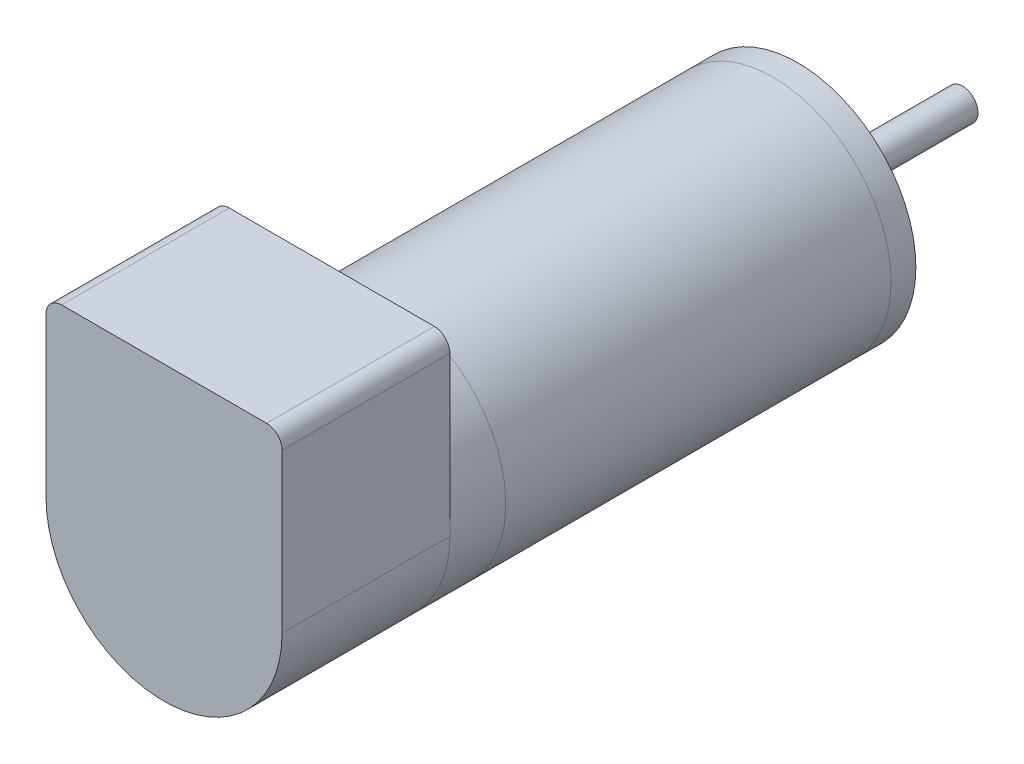
SolidWorks part; units mm, degrees
ref_plane "Front Plane" through (0, 0, 0) normal (0, 0, 1) x (1, 0, 0)
ref_plane "Top Plane" through (0, 0, 0) normal (0, 1, 0) x (1, 0, 0)
ref_plane "Right Plane" through (0, 0, 0) normal (1, 0, 0) x (0, 0, -1)
sketch "Sketch1" plane through (0, 0, 0) normal (1, 0, 0) x (0, 0, -1)
  line L0 (0, 0) -> (101.5, 0) construction
  line L1 (0, 0) -> (0, 19)
  line L2 (0, 19) -> (75, 19)
  line L3 (75, 19) -> (75, 6.25)
  line L4 (75, 6.25) -> (76.5, 6.25)
  line L5 (76.5, 6.25) -> (76.5, 2.5)
  line L6 (76.5, 2.5) -> (101.5, 2.5)
  line L7 (101.5, 2.5) -> (101.5, 0)
  line L8 (0, 0) -> (101.5, 0)
  dimension "D1" = 19
  dimension "D2" = 75
  dimension "D3" = 6.25
  dimension "D4" = 1.5
  dimension "D5" = 25
  dimension "D6" = 2.5
revolve "Revolve1" add sketch "Sketch1" angle 360 about L0
sketch "Sketch2" plane through (0, 0, 0) normal (0, 0, 1) x (1, 0, 0)
  line L0 (-19, 0) -> (-19, 25.5)
  line L1 (-16.5, 28) -> (16.5, 28)
  line L2 (19, 25.5) -> (19, 0)
  circle A0 centre (0, 0) radius 19 construction
  arc A1 (-19, 0) -> (19, 0) centre (0, 0) ccw
  arc A2 (19, 25.5) -> (16.5, 28) centre (16.5, 25.5) ccw
  arc A3 (-19, 25.5) -> (-16.5, 28) centre (-16.5, 25.5) cw
  point P5 (0, -19)
  dimension "D2" = 2.5
  dimension "D1" = 47
extrude "Boss-Extrude1" add sketch "Sketch2" along normal blind 27
sketch "Sketch3" plane through (0, 0, 0) normal (1, 0, 0) x (0, 0, -1)
  line L0 (71, 19) -> (71, -19)
  line L1 (-27, -19) -> (75, -19) construction
  line L2 (75, 19) -> (0, 19) construction
  line L3 (9, 19) -> (9, -19)
  line L4 (0, 19) -> (0, -19)
  line L5 (0, 25.5) -> (0, 0) construction
  line L6 (75, -19) -> (75, 19) construction
  dimension "D1" = 4
  dimension "D2" = 9
split line "Split Line1"
sketch "Sketch4" plane through (0, 0, -75) normal (0, 0, -1) x (-1, 0, 0)
  line L0 (-8.8388, 8.8388) -> (0, 0) construction
  line L1 (0, 0) -> (-19, 0) construction
  circle A0 centre (-8.8388, 8.8388) radius 1.5
  circle A1 centre (8.8388, 8.8388) radius 1.5
  circle A2 centre (8.8388, -8.8388) radius 1.5
  circle A3 centre (-8.8388, -8.8388) radius 1.5
  point P15 (0, 0)
  dimension "D2" = 3
  dimension "D1" = 45
  dimension "D3" = 12.5
  dimension "D4" = 4
extrude "Cut-Extrude1" cut sketch "Sketch4" against normal blind 10
